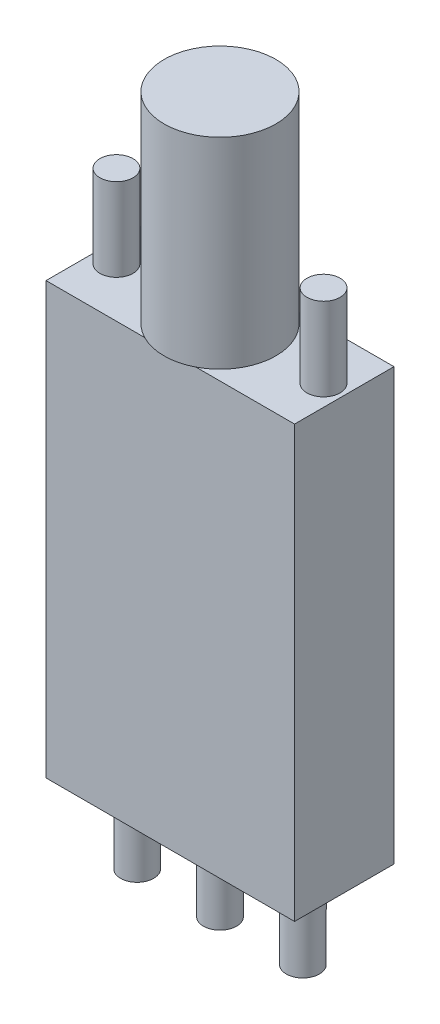
SolidWorks part; units mm, degrees
ref_plane "Front Plane" through (0, 0, 0) normal (0, 0, 1) x (1, 0, 0)
ref_plane "Top Plane" through (0, 0, 0) normal (0, 1, 0) x (1, 0, 0)
ref_plane "Right Plane" through (0, 0, 0) normal (1, 0, 0) x (0, 0, -1)
sketch "Sketch1" plane through (0, 0, 0) normal (0, 0, 1) x (1, 0, 0)
  line L1 (-7.5, -13) -> (7.5, -13)
  line L2 (-7.5, -13) -> (-7.5, 13)
  line L3 (-7.5, 13) -> (7.5, 13)
  line L4 (7.5, -13) -> (7.5, 13)
  line L5 (-7.5, -13) -> (7.5, 13) construction
  line L6 (-7.5, 13) -> (7.5, -13) construction
  point P0 (0, 0)
  dimension "D1" = 26
  dimension "D2" = 15
extrude "Boss-Extrude1" add sketch "Sketch1" along normal blind 6
sketch "Sketch2" plane through (0, 13, 0) normal (0, 1, 0) x (1, 0, 0)
  line L0 (-7.5, -3) -> (7.5, -3) construction
  line L3 (0, -3) -> (0, 0) construction
  line L4 (7.5, 0) -> (-7.5, 0) construction
  line L5 (-7.5, -6) -> (-7.5, 0) construction
  circle A0 centre (-6.25, -3) radius 1
  circle A1 centre (6.25, -3) radius 1
  dimension "D1" = 2
  dimension "D2" = 1.25
  dimension "D3" = 3
extrude "Boss-Extrude2" add sketch "Sketch2" along normal blind 5
sketch "Sketch3" plane through (0, -13, 0) normal (0, -1, 0) x (1, 0, 0)
  line L0 (-7.5, 3) -> (7.5, 3) construction
  line L1 (-7.5, 6) -> (-7.5, 0) construction
  line L2 (7.5, 6) -> (7.5, 0) construction
  line L3 (-7.5, 0) -> (7.5, 0) construction
  line L4 (0, 3) -> (0, 6) construction
  line L5 (-7.5, 6) -> (7.5, 6) construction
  circle A0 centre (0, 3) radius 1
  circle A1 centre (5, 3) radius 1
  circle A2 centre (-5, 3) radius 1
  dimension "D1" = 2
  dimension "D2" = 3
  dimension "D3" = 2
  dimension "D4" = 2
extrude "Boss-Extrude3" add sketch "Sketch3" along normal blind 5
sketch "Sketch4" plane through (0, 13, 0) normal (0, 1, 0) x (1, 0, 0)
  line L0 (-7.5, -3) -> (7.5, -3) construction
  line L1 (-7.5, -6) -> (-7.5, 0) construction
  line L2 (7.5, -6) -> (7.5, 0) construction
  line L3 (0, 0) -> (0, -6) construction
  line L4 (7.5, -6) -> (-7.5, -6) construction
sketch "Sketch5" plane through (0, 13, 0) normal (0, 1, 0) x (1, 0, 0)
  line L0 (0, 0) -> (0, -6) construction
  line L1 (-7.5, -3) -> (7.5, -3) construction
  circle A0 centre (0, -3) radius 3.375
  dimension "D1" = 6.75
extrude "Boss-Extrude4" add sketch "Sketch5" along normal blind 12.125
